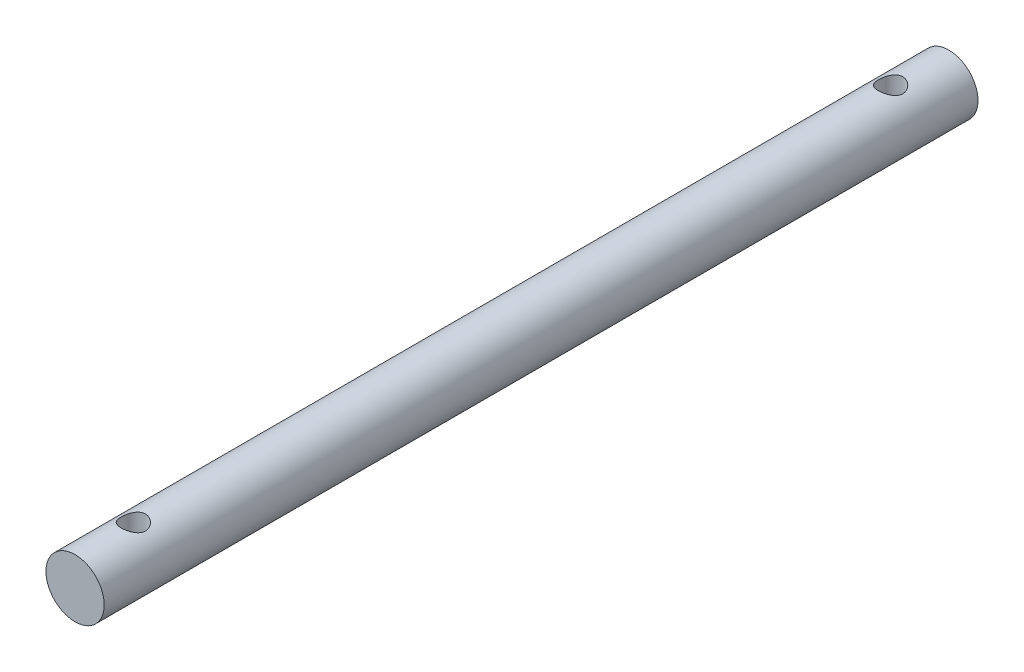
SolidWorks part; units mm, degrees
ref_plane "Front Plane" through (0, 0, 0) normal (0, 0, 1) x (1, 0, 0)
ref_plane "Top Plane" through (0, 0, 0) normal (0, 1, 0) x (1, 0, 0)
ref_plane "Right Plane" through (0, 0, 0) normal (1, 0, 0) x (0, 0, -1)
sketch "Sketch1" plane through (0, 0, 0) normal (0, 0, 1) x (1, 0, 0)
  circle A0 centre (0, 0) radius 5
  dimension "D1" = 10
extrude "Boss-Extrude1" add sketch "Sketch1" along normal mid plane 150
sketch "Sketch2" plane through (0, 0, 0) normal (0, 1, 0) x (1, 0, 0)
  line L0 (0, 0) -> (0, 65) construction
  line L1 (-5.6993, 0) -> (5, 0) construction
  line L2 (5, -75) -> (5, 75) construction
  circle A0 centre (0, 65) radius 2.0828
  circle A1 centre (0, -65) radius 2.0828
  dimension "D2" = 4.1656
  dimension "D1" = 65
extrude "Cut-Extrude1" cut sketch "Sketch2" against normal through all both and the other way through all
